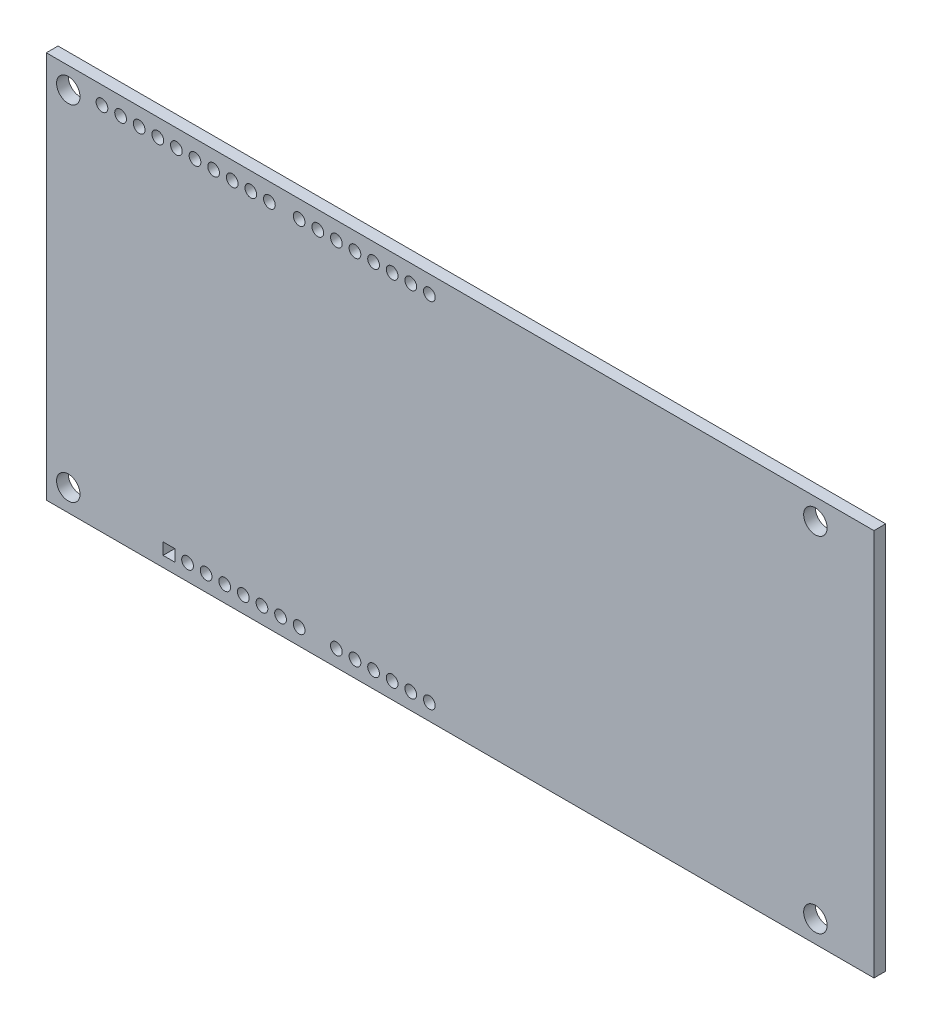
SolidWorks part; units mm, degrees
ref_plane "Plan de face" through (0, 0, 0) normal (0, 0, 1) x (1, 0, 0)
ref_plane "Plan de dessus" through (0, 0, 0) normal (0, 1, 0) x (1, 0, 0)
ref_plane "Plan de droite" through (0, 0, 0) normal (1, 0, 0) x (0, 0, -1)
sketch "Model" plane through (0, 0, 0) normal (0, 0, 1) x (1, 0, 0)
  line L72 (15.94, 3.04) -> (17.54, 3.04)
  line L73 (17.54, 3.04) -> (17.54, 1.44)
  line L74 (17.54, 1.44) -> (15.94, 1.44)
  line L75 (15.94, 1.44) -> (15.94, 3.04)
  line L76 (0, 0) -> (0, 52.9)
  line L77 (0, 52.9) -> (113, 52.9)
  line L78 (113, 52.9) -> (113, 0)
  line L79 (113, 0) -> (0, 0)
  circle A31 centre (52.3, 50.5) radius 0.8
  circle A32 centre (49.76, 50.5) radius 0.8
  circle A33 centre (47.22, 50.5) radius 0.8
  circle A34 centre (44.68, 50.5) radius 0.8
  circle A35 centre (42.14, 50.5) radius 0.8
  circle A36 centre (39.6, 50.5) radius 0.8
  circle A37 centre (37.06, 50.5) radius 0.8
  circle A38 centre (34.52, 50.5) radius 0.8
  circle A39 centre (30.46, 50.5) radius 0.8
  circle A40 centre (27.92, 50.5) radius 0.8
  circle A41 centre (25.38, 50.5) radius 0.8
  circle A42 centre (22.84, 50.5) radius 0.8
  circle A43 centre (20.3, 50.5) radius 0.8
  circle A44 centre (17.76, 50.5) radius 0.8
  circle A45 centre (15.22, 50.5) radius 0.8
  circle A46 centre (12.68, 50.5) radius 0.8
  circle A47 centre (10.14, 50.5) radius 0.8
  circle A48 centre (7.6, 50.5) radius 0.8
  circle A49 centre (19.28, 2.24) radius 0.8
  circle A50 centre (21.82, 2.24) radius 0.8
  circle A51 centre (24.36, 2.24) radius 0.8
  circle A52 centre (26.9, 2.24) radius 0.8
  circle A53 centre (29.44, 2.24) radius 0.8
  circle A54 centre (31.98, 2.24) radius 0.8
  circle A55 centre (34.52, 2.24) radius 0.8
  circle A56 centre (39.6, 2.24) radius 0.8
  circle A57 centre (42.14, 2.24) radius 0.8
  circle A58 centre (44.68, 2.24) radius 0.8
  circle A59 centre (47.22, 2.24) radius 0.8
  circle A60 centre (49.76, 2.24) radius 0.8
  circle A61 centre (52.3, 2.24) radius 0.8
  circle A62 centre (105, 3) radius 1.6
  circle A63 centre (105, 50) radius 1.6
  circle A64 centre (3, 50) radius 1.6
  circle A65 centre (3, 3) radius 1.6
extrude "Boss.-Extru.1" add sketch "Model" along normal blind 1.6
